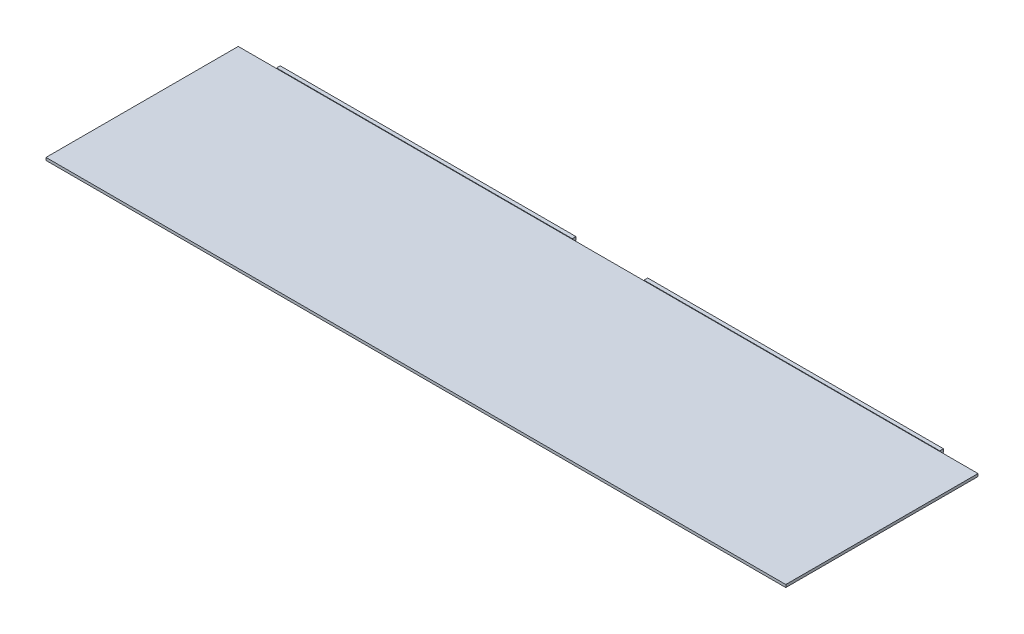
SolidWorks part; units mm, degrees
material "6061-T6 (SS)"
ref_plane "X-Y Datum" through (0, 0, 0) normal (0, 0, 1) x (1, 0, 0)
ref_plane "X-Z Datum" through (0, 0, 0) normal (0, 1, 0) x (1, 0, 0)
ref_plane "Y-Z Datum" through (0, 0, 0) normal (1, 0, 0) x (0, 0, -1)
sketch "Sketch1" plane through (0, 0, 0) normal (0, 1, 0) x (1, 0, 0)
  line L1 (-317.6778, 82.55) -> (317.6778, 82.55)
  line L2 (-317.6778, 82.55) -> (-317.6778, -82.55)
  line L3 (-317.6778, -82.55) -> (317.6778, -82.55)
  line L4 (317.6778, 82.55) -> (317.6778, -82.55)
  line L5 (-317.6778, 82.55) -> (317.6778, -82.55) construction
  line L6 (-317.6778, -82.55) -> (317.6778, 82.55) construction
  point P0 (0, 0)
  dimension "D1" = 635.3556
  dimension "D2" = 165.1
extrude "Boss-Extrude1" add sketch "Sketch1" along normal mid plane 2.286
sketch "Sketch2" plane through (0, 0, -82.55) normal (0, 0, -1) x (-1, 0, 0)
  line L20 (-317.6778, -1.143) -> (317.6778, -1.143) construction
  line L21 (-284.8229, -1.143) -> (-30.8229, -1.143)
  line L22 (30.8229, -1.143) -> (284.8229, -1.143)
  line L40 (30.8229, -1.143) -> (30.8229, 1.5875)
  line L41 (30.8229, 1.5875) -> (284.8229, 1.5875)
  line L42 (284.8229, 1.5875) -> (284.8229, -1.143)
  line L56 (-284.8229, -1.143) -> (-284.8229, 1.5875)
  line L57 (-284.8229, 1.5875) -> (-30.8229, 1.5875)
  line L58 (-30.8229, 1.5875) -> (-30.8229, -1.143)
extrude "Boss-Extrude2" add sketch "Sketch2" along normal blind 3.175
